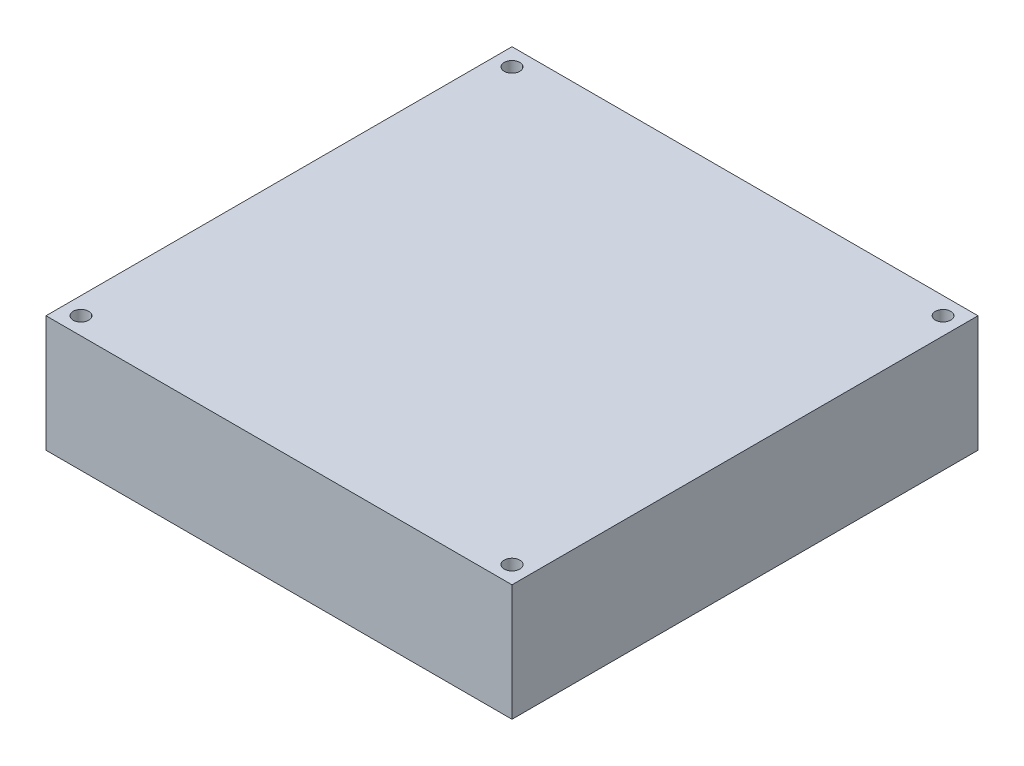
SolidWorks part; units mm, degrees
ref_plane "Front Plane" through (0, 0, 0) normal (0, 0, 1) x (1, 0, 0)
ref_plane "Top Plane" through (0, 0, 0) normal (0, 1, 0) x (1, 0, 0)
ref_plane "Right Plane" through (0, 0, 0) normal (1, 0, 0) x (0, 0, -1)
sketch "Sketch1" plane through (0, 0, 0) normal (0, 1, 0) x (1, 0, 0)
  line L1 (0, 0) -> (-60, 0)
  line L2 (0, 0) -> (0, 60)
  line L3 (0, 60) -> (-60, 60)
  line L4 (-60, 0) -> (-60, 60)
  dimension "D1" = 60
  dimension "D2" = 60
extrude "Boss-Extrude1" add sketch "Sketch1" along normal blind 15
sketch "Sketch2" plane through (0, 15, 0) normal (0, 1, 0) x (1, 0, 0)
  text T0 "H-Bridge" font "Century Gothic" height in points 16
sketch "Sketch3" plane through (0, 15, 0) normal (0, 1, 0) x (1, 0, 0)
  line L0 (-60, 60) -> (-60, 55.5)
  line L1 (-60, 60) -> (-60, 0) construction
  line L2 (0, 60) -> (0, 55.5)
  line L3 (0, 0) -> (0, 60) construction
  line L4 (-60, 60) -> (-55.5, 60)
  line L5 (0, 60) -> (-60, 60) construction
  line L6 (0, 60) -> (-4.5, 60)
  line L7 (-60, 0) -> (-55.5, 0)
  line L8 (-60, 0) -> (0, 0) construction
  line L9 (-55.5, 0) -> (-60, 0)
  line L10 (0, 0) -> (-4.5, 0)
  line L11 (-60, 0) -> (-60, 4.5)
  line L12 (0, 0) -> (0, 4.5)
  line L13 (-60, 2.25) -> (0, 2.25) construction
  line L14 (-57.75, 60) -> (-57.75, 0) construction
  line L15 (-2.25, 60) -> (-2.25, 0) construction
  line L16 (-60, 57.75) -> (0, 57.75) construction
  circle A0 centre (-57.75, 57.75) radius 1.0032
  circle A1 centre (-2.25, 57.75) radius 0.9909
  circle A2 centre (-2.25, 2.25) radius 1.009
  circle A3 centre (-57.75, 2.25) radius 1.0017
  dimension "D1" = 4.5
  dimension "D2" = 4.5
  dimension "D3" = 4.5
  dimension "D4" = 4.5
extrude "Cut-Extrude1" cut sketch "Sketch3" against normal through all contours A3 | A0 | A1 | A2
equation "\"D1@Sketch3\"=4.5mm"
equation "\"D2@Sketch3\"=4.5mm"
equation "\"D3@Sketch3\"=4.5mm"
equation "\"D4@Sketch3\"=4.5mm"
